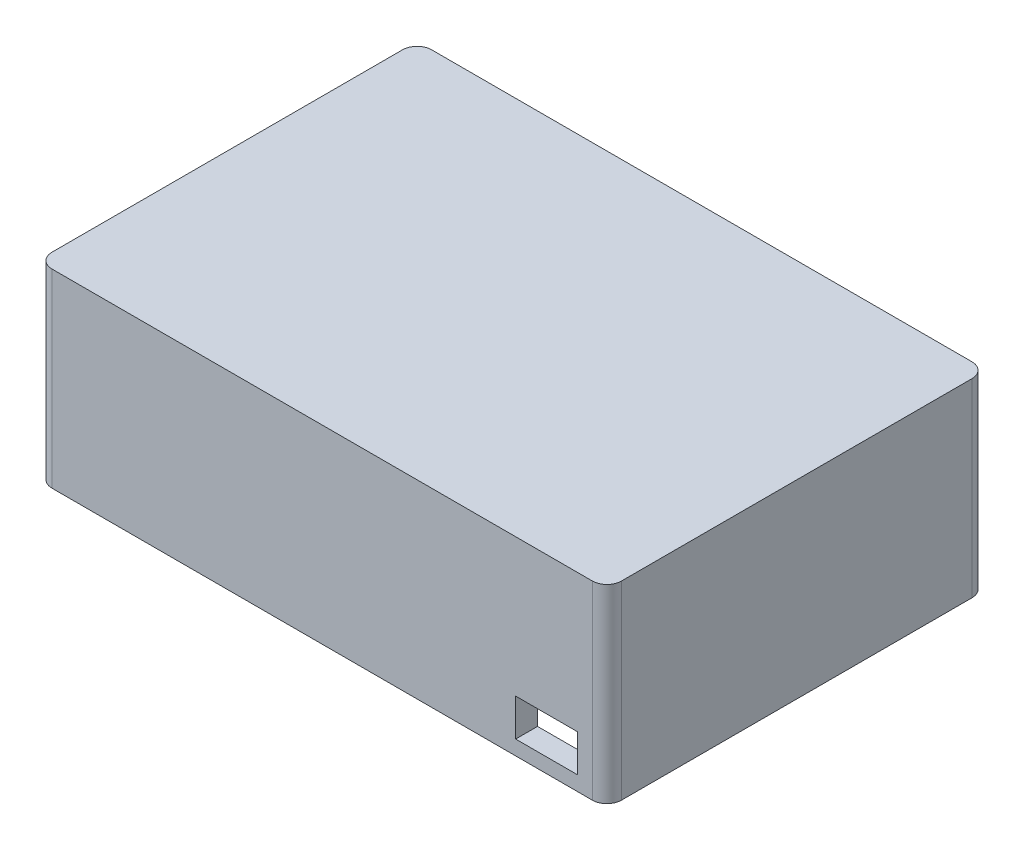
SolidWorks part; units mm, degrees
ref_plane "Front Plane" through (0, 0, 0) normal (0, 0, 1) x (1, 0, 0)
ref_plane "Top Plane" through (0, 0, 0) normal (0, 1, 0) x (1, 0, 0)
ref_plane "Right Plane" through (0, 0, 0) normal (1, 0, 0) x (0, 0, -1)
sketch "Sketch1" plane through (0, 0, 0) normal (0, 1, 0) x (1, 0, 0)
  line L1 (-51.6248, 27.9951) -> (47.4352, 27.9951)
  line L2 (-51.6248, 27.9951) -> (-51.6248, -38.0449)
  line L3 (-51.6248, -38.0449) -> (47.4352, -38.0449)
  line L4 (47.4352, 27.9951) -> (47.4352, -38.0449)
  dimension "D1" = 99.06
  dimension "D2" = 66.04
extrude "Boss-Extrude1" add sketch "Sketch1" along normal blind 33.02
fillet "Fillet1" radius 2.54 4 edges at (-51.6248, 16.51, 38.0449) (-51.6248, 16.51, -27.9951) (47.4352, 16.51, -27.9951) (47.4352, 16.51, 38.0449)
sketch "Sketch3" plane through (0, 0, 0) normal (0, -1, 0) x (1, 0, 0)
  line L0 (-2.0948, 34.2349) -> (-2.0948, 38.0449) construction
  line L1 (43.6252, 34.2349) -> (-47.8148, 34.2349)
  line L2 (43.6252, 34.2349) -> (43.6252, -24.1851)
  line L3 (43.6252, -24.1851) -> (-47.8148, -24.1851)
  line L4 (-47.8148, 34.2349) -> (-47.8148, -24.1851)
  line L5 (-2.0948, -24.1851) -> (-2.0948, -27.9951) construction
  line L6 (43.6252, 5.0249) -> (47.4352, 5.0249) construction
  line L7 (-51.6248, 5.0249) -> (-47.8148, 5.0249) construction
  line L10 (-51.6248, -25.4551) -> (-51.6248, 35.5049) construction
  line L11 (44.8952, -27.9951) -> (-49.0848, -27.9951) construction
  line L12 (47.4352, 35.5049) -> (47.4352, -25.4551) construction
  line L13 (-49.0848, 38.0449) -> (44.8952, 38.0449) construction
  line L14 (-51.6248, -25.4551) -> (-51.6248, 35.5049) construction
  line L15 (44.8952, -27.9951) -> (-49.0848, -27.9951) construction
  line L16 (47.4352, 35.5049) -> (47.4352, -25.4551) construction
  line L17 (-49.0848, 38.0449) -> (44.8952, 38.0449) construction
  point P4 (-10.9848, 5.0249)
  dimension "D1" = 3.81
extrude "Cut-Extrude1" cut sketch "Sketch3" against normal blind 30.48
sketch "Sketch7" plane through (0, 0, 0) normal (0, -1, 0) x (1, 0, 0)
  line L0 (43.6252, 34.2349) -> (-47.8148, 34.2349) construction
  line L1 (43.6252, -24.1851) -> (43.6252, 34.2349) construction
  line L2 (43.6252, 34.2349) -> (41.8292, 32.4389) construction
  line L3 (43.6252, 34.2349) -> (41.0852, 34.2349)
  line L4 (43.6252, 34.2349) -> (43.6252, 31.6949)
  line L5 (-47.8148, 34.2349) -> (-47.8148, -24.1851) construction
  line L6 (-47.8148, 34.2349) -> (-45.2748, 34.2349)
  line L7 (-47.8148, 34.2349) -> (-47.8148, 31.6949)
  line L8 (-47.8148, -24.1851) -> (43.6252, -24.1851) construction
  line L9 (-47.8148, -21.6451) -> (-47.8148, -24.1851)
  line L10 (-47.8148, -24.1851) -> (-45.2748, -24.1851)
  line L11 (41.0852, -24.1851) -> (43.6252, -24.1851)
  line L12 (43.6252, -24.1851) -> (43.6252, -21.6451)
  arc A0 (43.6252, 31.6949) -> (41.0852, 34.2349) centre (43.6252, 34.2349) cw
  arc A1 (-47.8148, 31.6949) -> (-45.2748, 34.2349) centre (-47.8148, 34.2349) ccw
  arc A2 (-45.2748, -24.1851) -> (-47.8148, -21.6451) centre (-47.8148, -24.1851) ccw
  arc A3 (43.6252, -21.6451) -> (41.0852, -24.1851) centre (43.6252, -24.1851) ccw
  dimension "D1" = 2.54
extrude "Boss-Extrude2" add sketch "Sketch7" against normal up to next
sketch "Sketch4" plane through (0, 0, 0) normal (0, -1, 0) x (1, 0, 0)
  line L0 (-48.4498, -24.8201) -> (-46.0187, -22.389) construction
  line L1 (44.2602, 34.8699) -> (-48.4498, 34.8699) construction
  line L2 (44.2602, 34.8699) -> (44.2602, -24.8201) construction
  line L3 (44.2602, -24.8201) -> (-48.4498, -24.8201) construction
  line L4 (-48.4498, 34.8699) -> (-48.4498, -24.8201) construction
  line L5 (-50.8808, -27.2511) -> (-48.4498, -24.8201) construction
  line L6 (41.8292, 32.4389) -> (44.2602, 34.8699)
  line L10 (44.2602, 34.8699) -> (46.6913, 37.301) construction
  circle A0 centre (44.2602, 34.8699) radius 1.1906
  circle A1 centre (44.2602, -24.8201) radius 1.1906
  circle A2 centre (-48.4498, 34.8699) radius 1.1906
  circle A3 centre (-48.4498, -24.8201) radius 1.1906
  arc A4 (47.4352, 35.5049) -> (44.8952, 38.0449) centre (44.8952, 35.5049) ccw construction
  arc A6 (41.0852, 34.2349) -> (43.6252, 31.6949) centre (43.6252, 34.2349) ccw construction
  arc A7 (41.0852, 34.2349) -> (43.6252, 31.6949) centre (43.6252, 34.2349) ccw construction
  arc A8 (-45.2748, -24.1851) -> (-47.8148, -21.6451) centre (-47.8148, -24.1851) ccw construction
  arc A9 (-45.2748, -24.1851) -> (-47.8148, -21.6451) centre (-47.8148, -24.1851) ccw construction
  arc A10 (-51.6248, -25.4551) -> (-49.0848, -27.9951) centre (-49.0848, -25.4551) ccw construction
  dimension "D1" = 2.3813
extrude "Cut-Extrude5" cut sketch "Sketch4" against normal blind 12.7 contours A0 | A1 | A2 | A3
sketch "Sketch6" plane through (0, 0, 38.0449) normal (0, 0, 1) x (1, 0, 0)
  line L0 (44.8952, 5.7785) -> (42.3552, 5.7785) construction
  line L1 (42.3552, 2.54) -> (31.5602, 2.54)
  line L2 (42.3552, 2.54) -> (42.3552, 9.017)
  line L3 (42.3552, 9.017) -> (31.5602, 9.017)
  line L4 (31.5602, 2.54) -> (31.5602, 9.017)
  line L5 (44.8952, 0) -> (44.8952, 33.02) construction
  line L6 (36.9577, 2.54) -> (36.9577, 0) construction
  line L7 (-49.0848, 0) -> (44.8952, 0) construction
  point P10 (36.0786, 1.4838)
  dimension "D1" = 10.795
  dimension "D2" = 6.477
  dimension "D3" = 2.54
extrude "Cut-Extrude4" cut sketch "Sketch6" against normal up to next
